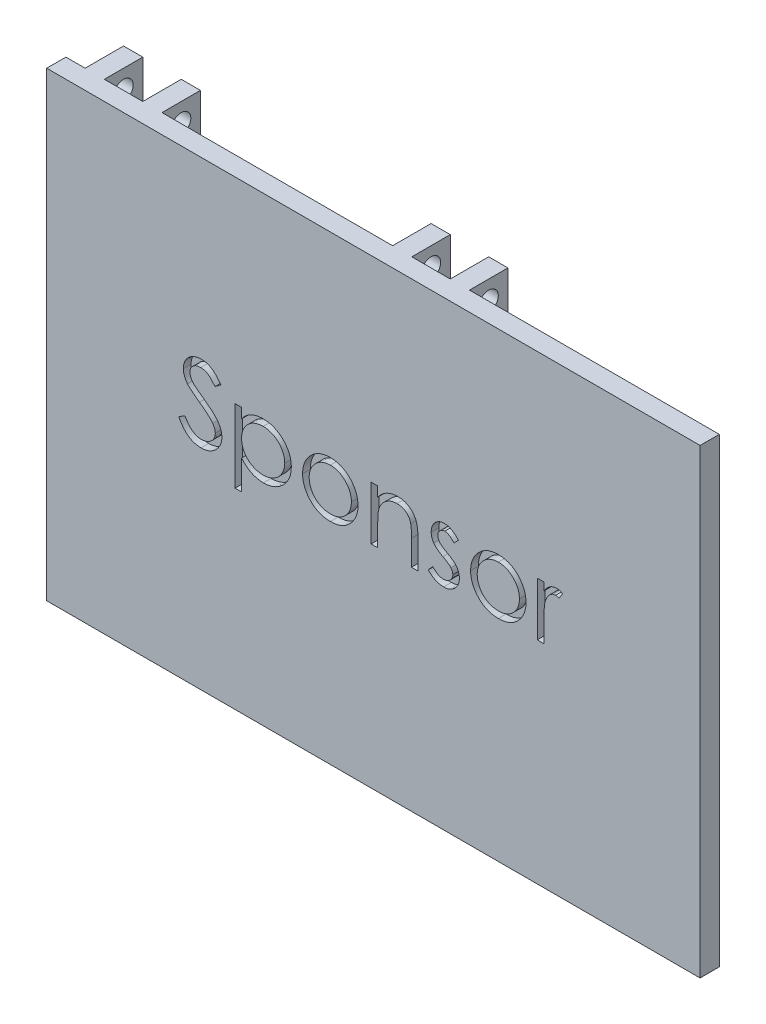
SolidWorks part; units mm, degrees
ref_plane "Plan de face" through (0, 0, 0) normal (0, 0, 1) x (1, 0, 0)
ref_plane "Plan de dessus" through (0, 0, 0) normal (0, 1, 0) x (1, 0, 0)
ref_plane "Plan de droite" through (0, 0, 0) normal (1, 0, 0) x (0, 0, -1)
sketch "Esquisse1" plane through (0, 0, 0) normal (0, 0, 1) x (1, 0, 0)
  line L1 (85, 60) -> (-85, 60)
  line L2 (85, 60) -> (85, -60)
  line L3 (85, -60) -> (-85, -60)
  line L4 (-85, 60) -> (-85, -60)
  line L5 (85, 60) -> (-85, -60) construction
  line L6 (85, -60) -> (-85, 60) construction
  point P0 (0, 0)
  dimension "D1" = 120
  dimension "D2" = 170
extrude "BASE" add sketch "Esquisse1" along normal blind 5
sketch "Esquisse2" plane through (0, 60, 0) normal (0, 1, 0) x (1, 0, 0)
  line L0 (85, 0) -> (-85, 0) construction
  line L2 (-75, 10) -> (-75, 0)
  line L3 (-75, 0) -> (-80, 0)
  line L4 (-65, 10) -> (-65, 0)
  line L5 (-65, 0) -> (-60, 0)
  line L6 (-80, 0) -> (-80, 10)
  line L7 (-80, 10) -> (-75, 10)
  line L8 (-60, 0) -> (-60, 10)
  line L9 (-60, 10) -> (-65, 10)
  line L10 (-30, 15.4912) -> (-30, -31.7182) construction
  line L12 (0, 10) -> (5, 10)
  line L13 (0, 0) -> (0, 10)
  line L14 (20, 10) -> (15, 10)
  line L15 (20, 0) -> (20, 10)
  line L16 (0, 0) -> (5, 0)
  line L17 (5, 10) -> (5, 0)
  line L18 (15, 0) -> (20, 0)
  line L19 (15, 10) -> (15, 0)
  line L20 (15, 0) -> (20, 0)
  line L21 (-85, -5) -> (-85, 0) construction
  point P0 (10, 0)
  point P1 (-70, 0)
  point P4 (-85, -2.5)
  line M1 (85, 0) -> (-85, 0)
  dimension "D1" = 15
  dimension "D2" = 50
  dimension "D3" = 5
  dimension "D4" = 5
  dimension "D5" = 5
  dimension "D6" = 5
  dimension "D7" = 10
  dimension "D8" = 10
extrude "BOSS TIGE" add sketch "Esquisse2" against normal blind 10 contours L14 L19 L15 M1 | L17 L12 L13 M1 | L8 L9 L4 M1 | L7 L6 L2 M1
sketch "Esquisse4" plane through (0, 0, 5) normal (0, 0, 1) x (1, 0, 0)
  line L0 (-51.1463, -4.9958) -> (58.7709, -4.9958) construction
  text T0 "Sponsor" font "Century Gothic" height in points 72
extrude "VIDE SPONSOR" cut sketch "Esquisse4" against normal blind 2
sketch "Esquisse5" plane through (20, 0, 0) normal (1, 0, 0) x (0, 0, -1)
  line L0 (0, 60) -> (10, 50) construction
  line L1 (10, 50) -> (10, 55) construction
  line L2 (10, 50) -> (10, 60) construction
  line L3 (10, 55) -> (5, 55) construction
  circle A0 centre (5, 55) radius 2.5
  dimension "D1" = 5
extrude "Enlèv. mat.-Extru.3" cut sketch "Esquisse5" against normal through all
